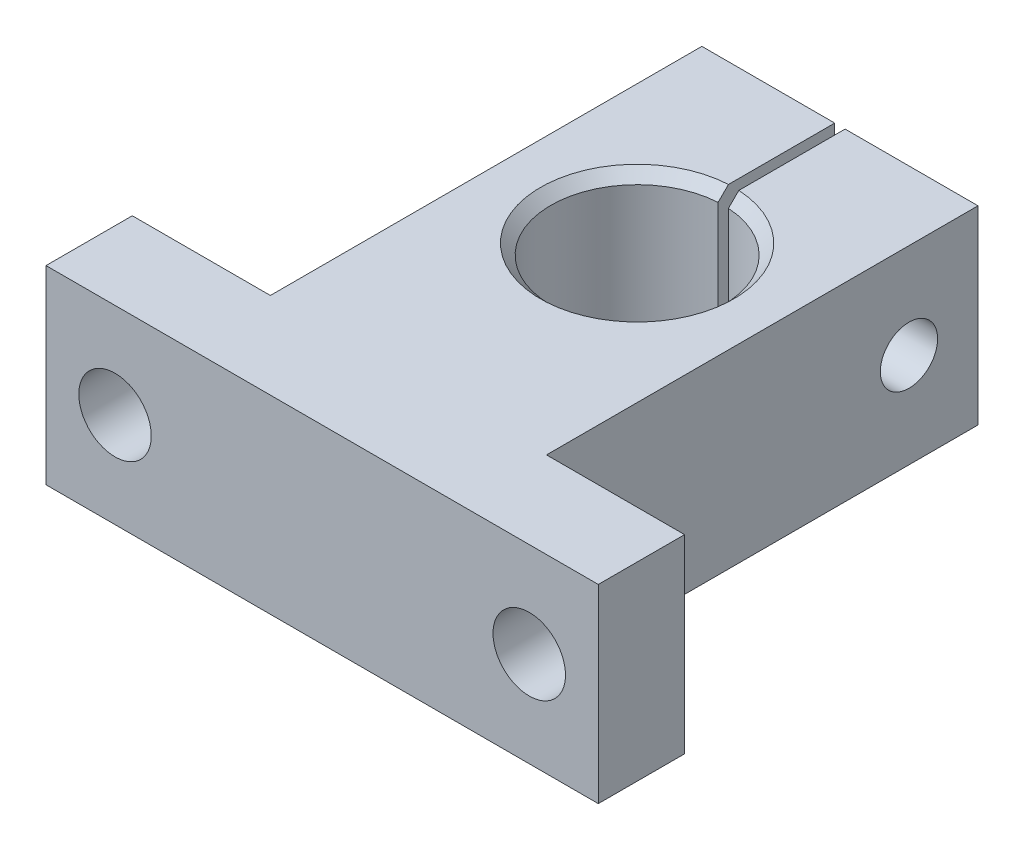
SolidWorks part; units mm, degrees
material "6061 Alloy"
ref_plane "Front Plane" through (0, 0, 0) normal (0, 0, 1) x (1, 0, 0)
ref_plane "Top Plane" through (0, 0, 0) normal (0, 1, 0) x (1, 0, 0)
ref_plane "Right Plane" through (0, 0, 0) normal (1, 0, 0) x (0, 0, -1)
sketch "Sketch1" plane through (0, 0, 0) normal (0, 1, 0) x (1, 0, 0)
  line L0 (0, 6.0325) -> (0, 14.9225) construction
  line L1 (10.16, 14.9225) -> (0.381, 14.9225)
  line L2 (-10.16, 14.9225) -> (-10.16, -16.8275)
  line L3 (10.16, 14.9225) -> (10.16, -16.8275)
  line L4 (10.16, -16.8275) -> (20.32, -16.8275)
  line L5 (20.32, -16.8275) -> (20.32, -23.1775)
  line L6 (20.32, -23.1775) -> (-20.32, -23.1775)
  line L7 (-20.32, -23.1775) -> (-20.32, -16.8275)
  line L8 (-20.32, -16.8275) -> (-10.16, -16.8275)
  line L9 (0.381, 6.3386) -> (0.381, 14.9225)
  line L10 (-0.381, 6.3386) -> (-0.381, 14.9225)
  line L13 (-0.381, 14.9225) -> (-10.16, 14.9225)
  line L14 (-0.381, 6.0325) -> (-0.381, 14.9225) construction
  line L15 (0.381, 6.0325) -> (0.381, 14.9225) construction
  arc A0 (-0.381, 6.3386) -> (0.381, 6.3386) centre (0, 0) ccw
  point P8 (0, 14.9225)
  dimension "D1" = 12.7
  dimension "D2" = 8.89
  dimension "D3" = 20.32
  dimension "D4" = 0.381
  dimension "D5" = 0.381
extrude "Boss-Extrude1" add sketch "Sketch1" along normal blind 13.97
sketch "Sketch2" plane through (0, 0, 16.8275) normal (0, 0, -1) x (-1, 0, 0)
  line L0 (0, 0) -> (0, 13.97) construction
  line L1 (6.35, 13.97) -> (-6.35, 13.97) construction
  line L2 (15.24, 6.985) -> (-15.24, 6.985) construction
  circle A0 centre (-15.24, 6.985) radius 2.667
  circle A1 centre (15.24, 6.985) radius 2.667
  point P8 (0, 6.985)
  dimension "D1" = 5.334
  dimension "D2" = 5.334
  dimension "D3" = 30.48
extrude "Cut-Extrude1" cut sketch "Sketch2" against normal blind 13.97
sketch "Sketch3" plane through (-10.16, 0, 0) normal (-1, 0, 0) x (0, 0, 1)
  line L0 (-14.9225, 13.97) -> (-14.9225, 0) construction
  line L1 (-14.9225, 6.985) -> (-9.8425, 6.985) construction
  circle A0 centre (-9.8425, 6.985) radius 3.81
  dimension "D2" = 7.62
  dimension "D1" = 5.08
extrude "Cut-Extrude2" cut sketch "Sketch3" against normal blind 4.826
sketch "Sketch4" plane through (-5.334, 0, 0) normal (-1, 0, 0) x (0, 0, 1)
  circle A0 centre (-9.8425, 6.985) radius 2.1082
  dimension "D1" = 4.2164
extrude "Cut-Extrude3" cut sketch "Sketch4" against normal blind 17.272
chamfer "Chamfer1" distance 0.762 angle 45 5 edges at (-10.16, 6.985, -6.0325) (12.573, 6.985, 16.8275) (-17.907, 6.985, 16.8275) (0, 0, 6.35) (0, 13.97, 6.35)
